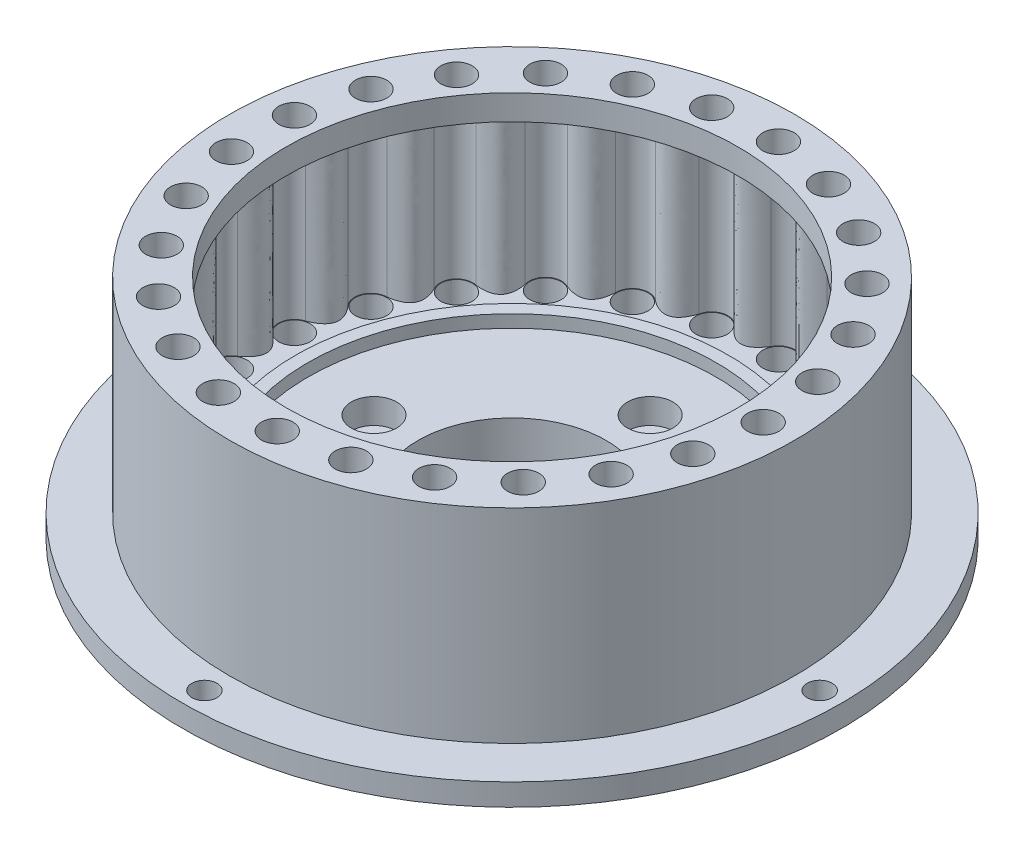
SolidWorks part; units mm, degrees
ref_plane "Front Plane" through (0, 0, 0) normal (0, 0, 1) x (1, 0, 0)
ref_plane "Top Plane" through (0, 0, 0) normal (0, 1, 0) x (1, 0, 0)
ref_plane "Right Plane" through (0, 0, 0) normal (1, 0, 0) x (0, 0, -1)
sketch "Sketch1" plane through (0, 0, 0) normal (0, 1, 0) x (1, 0, 0)
  circle A1 centre (0, 0) radius 45
  circle A2 centre (0, 0) radius 22 construction
  circle A3 centre (0, -22) radius 2
  circle A5 centre (-22, 0) radius 2
  circle A6 centre (0, 22) radius 2
  circle A7 centre (22, 0) radius 2
  point P15 (0, 0)
  dimension "D1" = 90
  dimension "D2" = 44
  dimension "D3" = 4
  dimension "D4" = 4
  dimension "D5" = 90
  dimension "D6" = 22
extrude "Boss-Extrude1" add sketch "Sketch1" along normal blind 6
sketch "Sketch2" plane through (0, 6, 0) normal (0, 1, 0) x (1, 0, 0)
  circle A0 centre (0, 0) radius 22 construction
  circle A1 centre (0, 22) radius 3.61
  circle A2 centre (22, 0) radius 3.61
  circle A3 centre (0, -22) radius 3.61
  circle A4 centre (-22, 0) radius 3.61
  point P14 (0, 0)
  dimension "D1" = 44
  dimension "D2" = 7.22
  dimension "D4" = 22
  dimension "D5" = 90
  dimension "D3" = 4
extrude "Cut-Extrude1" cut sketch "Sketch2" against normal blind 4
sketch "Sketch4" plane through (0, 6, 0) normal (0, 1, 0) x (1, 0, 0)
  circle A0 centre (0, 0) radius 15
  dimension "D1" = 30
extrude "Cut-Extrude2" cut sketch "Sketch4" against normal through all
sketch "Sketch5" plane through (0, 6, 0) normal (0, 1, 0) x (1, 0, 0)
  circle A0 centre (40, 0) radius 2.5
  circle A1 centre (38.7433, -9.9476) radius 2.5
  circle A2 centre (35.0523, -19.2701) radius 2.5
  circle A3 centre (29.1587, -27.3819) radius 2.5
  circle A4 centre (21.4331, -33.7731) radius 2.5
  circle A5 centre (12.3607, -38.0423) radius 2.5
  circle A6 centre (2.5116, -39.9211) radius 2.5
  circle A7 centre (-7.4953, -39.2915) radius 2.5
  circle A8 centre (-17.0312, -36.1931) radius 2.5
  circle A9 centre (-25.497, -30.8205) radius 2.5
  circle A10 centre (-32.3607, -23.5114) radius 2.5
  circle A11 centre (-37.1911, -14.725) radius 2.5
  circle A12 centre (-39.6846, -5.0133) radius 2.5
  circle A13 centre (-39.6846, 5.0133) radius 2.5
  circle A14 centre (-37.1911, 14.725) radius 2.5
  circle A15 centre (-32.3607, 23.5114) radius 2.5
  circle A16 centre (-25.497, 30.8205) radius 2.5
  circle A17 centre (-17.0312, 36.1931) radius 2.5
  circle A18 centre (-7.4953, 39.2915) radius 2.5
  circle A19 centre (2.5116, 39.9211) radius 2.5
  circle A20 centre (12.3607, 38.0423) radius 2.5
  circle A21 centre (21.4331, 33.7731) radius 2.5
  circle A22 centre (29.1587, 27.3819) radius 2.5
  circle A23 centre (35.0523, 19.2701) radius 2.5
  circle A24 centre (38.7433, 9.9476) radius 2.5
  point P53 (0, 0)
  dimension "D2" = 5
  dimension "D1" = 40
  dimension "D3" = 25
extrude "Cut-Extrude3" cut sketch "Sketch5" against normal blind 4
sketch "Sketch6" plane through (0, 6, 0) normal (0, 1, 0) x (1, 0, 0)
  circle A0 centre (0, 0) radius 32.5
  circle A1 centre (0, 0) radius 34.5
  dimension "D1" = 65
  dimension "D2" = 69
extrude "Boss-Extrude2" add sketch "Sketch6" along normal blind 2
sketch "Sketch7" plane through (0, 6, 0) normal (0, 1, 0) x (1, 0, 0)
  line L0 (0, 0) -> (35.0523, -19.2701) construction
  line L1 (0, 0) -> (27.3363, -25.6705) construction
  line L2 (35.0523, -19.2701) -> (34.7909, -21.7565) construction
  line L3 (29.1587, -27.3819) -> (31.4426, -26.365) construction
  line L4 (0, 0) -> (31.5517, -22.9236) construction
  circle A0 centre (35.0523, -19.2701) radius 2.5 construction
  circle A1 centre (38.7433, -9.9476) radius 2.5 construction
  circle A2 centre (40, 0) radius 2.5 construction
  circle A3 centre (38.7433, 9.9476) radius 2.5 construction
  circle A4 centre (35.0523, 19.2701) radius 2.5 construction
  circle A5 centre (29.1587, 27.3819) radius 2.5 construction
  circle A6 centre (21.4331, 33.7731) radius 2.5 construction
  circle A7 centre (12.3607, 38.0423) radius 2.5 construction
  circle A8 centre (2.5116, 39.9211) radius 2.5 construction
  circle A9 centre (-7.4953, 39.2915) radius 2.5 construction
  circle A10 centre (-17.0312, 36.1931) radius 2.5 construction
  circle A11 centre (-25.497, 30.8205) radius 2.5 construction
  circle A12 centre (-32.3607, 23.5114) radius 2.5 construction
  circle A13 centre (-37.1911, 14.725) radius 2.5 construction
  circle A14 centre (-39.6846, 5.0133) radius 2.5 construction
  circle A15 centre (-39.6846, -5.0133) radius 2.5 construction
  circle A16 centre (-37.1911, -14.725) radius 2.5 construction
  circle A17 centre (-32.3607, -23.5114) radius 2.5 construction
  circle A18 centre (-25.497, -30.8205) radius 2.5 construction
  circle A19 centre (-17.0312, -36.1931) radius 2.5 construction
  circle A20 centre (-7.4953, -39.2915) radius 2.5 construction
  circle A21 centre (2.5116, -39.9211) radius 2.5 construction
  circle A22 centre (12.3607, -38.0423) radius 2.5 construction
  circle A23 centre (21.4331, -33.7731) radius 2.5 construction
  circle A24 centre (29.1587, -27.3819) radius 2.5 construction
  arc A25 (34.7909, -21.7565) -> (37.0115, -17.7173) centre (35.0523, -19.2701) ccw construction
  arc A26 (39.1085, -12.4208) -> (40.2548, -7.9563) centre (38.7433, -9.9476) ccw construction
  arc A27 (40.9688, -2.3047) -> (40.9688, 2.3047) centre (40, 0) ccw construction
  arc A28 (40.2548, 7.9563) -> (39.1085, 12.4208) centre (38.7433, 9.9476) ccw construction
  arc A29 (37.0115, 17.7173) -> (34.7909, 21.7565) centre (35.0523, 19.2701) ccw construction
  arc A30 (31.4426, 26.365) -> (28.2873, 29.7251) centre (29.1587, 27.3819) ccw construction
  arc A31 (23.8981, 33.3562) -> (20.0063, 35.826) centre (21.4331, 33.7731) ccw construction
  arc A32 (14.8519, 38.2515) -> (10.4682, 39.6758) centre (12.3607, 38.0423) ccw construction
  arc A33 (4.8726, 40.7432) -> (0.2723, 41.0327) centre (2.5116, 39.9211) ccw construction
  arc A34 (-5.4129, 40.675) -> (-9.9406, 39.8113) centre (-7.4953, 39.2915) ccw construction
  arc A35 (-15.3583, 38.0509) -> (-19.529, 36.0884) centre (-17.0312, 36.1931) ccw construction
  arc A36 (-24.3387, 33.036) -> (-27.8903, 30.098) centre (-25.497, 30.8205) ccw construction
  arc A37 (-31.7898, 25.9454) -> (-34.4991, 22.2163) centre (-32.3607, 23.5114) ccw construction
  arc A38 (-37.2434, 17.2244) -> (-38.9402, 12.9388) centre (-37.1911, 14.725) ccw construction
  arc A39 (-40.3569, 7.4212) -> (-40.9346, 2.8483) centre (-39.6846, 5.0133) ccw construction
  arc A40 (-40.9346, -2.8483) -> (-40.3569, -7.4212) centre (-39.6846, -5.0133) ccw construction
  arc A41 (-38.9402, -12.9388) -> (-37.2434, -17.2244) centre (-37.1911, -14.725) ccw construction
  arc A42 (-34.4991, -22.2163) -> (-31.7898, -25.9454) centre (-32.3607, -23.5114) ccw construction
  arc A43 (-27.8903, -30.098) -> (-24.3387, -33.036) centre (-25.497, -30.8205) ccw construction
  arc A44 (-19.529, -36.0884) -> (-15.3583, -38.0509) centre (-17.0312, -36.1931) ccw construction
  arc A45 (-9.9406, -39.8113) -> (-5.4129, -40.675) centre (-7.4953, -39.2915) ccw construction
  arc A46 (0.2723, -41.0327) -> (4.8726, -40.7432) centre (2.5116, -39.9211) ccw construction
  arc A47 (10.4682, -39.6758) -> (14.8519, -38.2515) centre (12.3607, -38.0423) ccw construction
  arc A48 (20.0063, -35.826) -> (23.8981, -33.3562) centre (21.4331, -33.7731) ccw construction
  arc A49 (28.2873, -29.7251) -> (31.4426, -26.365) centre (29.1587, -27.3819) ccw construction
  arc A51 (33.4936, -21.8672) -> (35.0523, -19.2701) centre (0, 0) ccw construction
  arc A53 (23.9272, -32.0545) -> (27.0032, -29.5098) centre (0, 0) ccw construction
  arc A54 (15.2038, -36.9979) -> (18.8161, -35.2981) centre (0, 0) ccw construction
  arc A55 (9.9601, -38.7401) -> (14.713, -37.1958) centre (0, 0) ccw construction
  arc A56 (5.5252, -39.6166) -> (9.4467, -38.8685) centre (0, 0) ccw construction
  arc A57 (-5.0261, -39.683) -> (5.0006, -39.6862) centre (0, 0) ccw construction
  arc A58 (-14.7369, -37.1863) -> (-10.4469, -38.6117) centre (0, 0) ccw construction
  arc A59 (-23.0917, -32.6615) -> (-22.9047, -32.7929) centre (0, 0) ccw construction
  arc A60 (-30.4888, -25.8927) -> (-27.756, -28.8029) centre (0, 0) ccw construction
  arc A61 (-35.9702, -17.4969) -> (-34.047, -20.9953) centre (0, 0) ccw construction
  arc A62 (-39.1915, -8.0018) -> (-38.1986, -11.8686) centre (0, 0) ccw construction
  arc A63 (-39.9502, 1.9961) -> (-39.9502, -1.9961) centre (0, 0) ccw construction
  arc A64 (-38.1986, 11.8686) -> (-39.1915, 8.0018) centre (0, 0) ccw construction
  arc A65 (-36.1986, 17.0195) -> (-38.0383, 12.3729) centre (0, 0) ccw construction
  arc A66 (-34.047, 20.9953) -> (-35.9702, 17.4969) centre (0, 0) ccw construction
  arc A67 (-27.756, 28.8029) -> (-30.4888, 25.8927) centre (0, 0) ccw construction
  arc A68 (-19.2589, 35.0585) -> (-23.0917, 32.6615) centre (0, 0) ccw construction
  arc A69 (-9.9351, 38.7465) -> (-14.7369, 37.1863) centre (0, 0) ccw construction
  arc A70 (-0.5163, 39.9967) -> (-5.0261, 39.683) centre (0, 0) ccw construction
  arc A71 (9.4467, 38.8685) -> (0.0129, 40) centre (0, 0) ccw construction
  arc A72 (18.8161, 35.2981) -> (15.2038, 36.9979) centre (0, 0) ccw construction
  arc A73 (27.0032, 29.5098) -> (23.9272, 32.0545) centre (0, 0) ccw construction
  arc A74 (33.4936, 21.8672) -> (30.8123, 25.5069) centre (0, 0) ccw construction
  arc A75 (37.8795, 12.8507) -> (36.4099, 16.5626) centre (0, 0) ccw construction
  arc A76 (39.8853, 3.0267) -> (39.2891, 7.5079) centre (0, 0) ccw construction
  arc A77 (39.385, -6.9875) -> (39.9219, -2.4988) centre (0, 0) ccw construction
  arc A78 (36.1876, -17.0428) -> (37.8795, -12.8507) centre (0, 0) ccw construction
  circle A79 centre (0, 0) radius 45
  arc A80 (34.7861, -21.8565) -> (37.0934, -17.6596) centre (35.0523, -19.2701) ccw
  arc A81 (39.1287, -12.5189) -> (40.3198, -7.88) centre (38.7433, -9.9476) ccw
  arc A82 (41.0127, -2.3947) -> (41.0127, 2.3947) centre (40, 0) ccw
  arc A83 (40.3198, 7.88) -> (39.1287, 12.5189) centre (38.7433, 9.9476) ccw
  arc A84 (37.0934, 17.6596) -> (34.7861, 21.8565) centre (35.0523, 19.2701) ccw
  arc A85 (31.5362, 26.3295) -> (28.2577, 29.8208) centre (29.1587, 27.3819) ccw
  arc A86 (23.9976, 33.3451) -> (19.9538, 35.9113) centre (21.4331, 33.7731) ccw
  arc A87 (14.9511, 38.2654) -> (10.3962, 39.7454) centre (12.3607, 38.0423) ccw
  arc A88 (4.9651, 40.7814) -> (0.1853, 41.0822) centre (2.5116, 39.9211) ccw
  arc A89 (-5.3328, 40.735) -> (-10.0373, 39.8376) centre (-7.4953, 39.2915) ccw
  arc A90 (-15.2956, 38.129) -> (-19.6291, 36.0898) centre (-17.0312, 36.1931) ccw
  arc A91 (-24.2974, 33.1273) -> (-27.9876, 30.0744) centre (-25.497, 30.8205) ccw
  arc A92 (-31.7724, 26.044) -> (-34.5875, 22.1694) centre (-32.3607, 23.5114) ccw
  arc A93 (-37.2511, 17.3243) -> (-39.0142, 12.8713) centre (-37.1911, 14.725) ccw
  arc A94 (-40.3892, 7.516) -> (-40.9895, 2.7645) centre (-39.6846, 5.0133) ccw
  arc A95 (-40.9895, -2.7645) -> (-40.3892, -7.516) centre (-39.6846, -5.0133) ccw
  arc A96 (-39.0142, -12.8713) -> (-37.2511, -17.3243) centre (-37.1911, -14.725) ccw
  arc A97 (-34.5875, -22.1694) -> (-31.7724, -26.044) centre (-32.3607, -23.5114) ccw
  arc A98 (-27.9876, -30.0744) -> (-24.2974, -33.1273) centre (-25.497, -30.8205) ccw
  arc A99 (-19.6291, -36.0898) -> (-15.2956, -38.129) centre (-17.0312, -36.1931) ccw
  arc A100 (-10.0373, -39.8376) -> (-5.3328, -40.735) centre (-7.4953, -39.2915) ccw
  arc A101 (0.1853, -41.0822) -> (4.9651, -40.7814) centre (2.5116, -39.9211) ccw
  arc A102 (10.3962, -39.7454) -> (14.9511, -38.2654) centre (12.3607, -38.0423) ccw
  arc A103 (19.9538, -35.9113) -> (23.9976, -33.3451) centre (21.4331, -33.7731) ccw
  arc A104 (28.2577, -29.8208) -> (31.5362, -26.3295) centre (29.1587, -27.3819) ccw
  spline S0 degree 2 poles (34.7909, -21.7565) (29.9865, -21.7865) (31.4426, -26.365) knots 0 0 0 1 1 1 construction
  spline S1 degree 2 poles (28.2873, -29.7251) (23.6264, -28.5594) (23.8981, -33.3562) knots 0 0 0 1 1 1 construction
  spline S2 degree 2 poles (20.0063, -35.826) (15.7817, -33.5378) (14.8519, -38.2515) knots 0 0 0 1 1 1 construction
  spline S3 degree 2 poles (10.4682, -39.6758) (6.9454, -36.4089) (4.8726, -40.7432) knots 0 0 0 1 1 1 construction
  spline S4 degree 2 poles (0.2723, -41.0327) (-2.3274, -36.9923) (-5.4129, -40.675) knots 0 0 0 1 1 1 construction
  spline S5 degree 2 poles (-9.9406, -39.8113) (-11.4538, -35.2513) (-15.3583, -38.0509) knots 0 0 0 1 1 1 construction
  spline S6 degree 2 poles (-19.529, -36.0884) (-19.8606, -31.2954) (-24.3387, -33.036) knots 0 0 0 1 1 1 construction
  spline S7 degree 2 poles (-27.8903, -30.098) (-27.0195, -25.373) (-31.7898, -25.9454) knots 0 0 0 1 1 1 construction
  spline S8 degree 2 poles (-34.4991, -22.2163) (-32.4807, -17.8564) (-37.2434, -17.2244) knots 0 0 0 1 1 1 construction
  spline S9 degree 2 poles (-38.9402, -12.9388) (-35.9009, -9.2178) (-40.3569, -7.4212) knots 0 0 0 1 1 1 construction
  spline S10 degree 2 poles (-40.9346, -2.8483) (-37.0654, 0) (-40.9346, 2.8483) knots 0 0 0 1 1 1 construction
  spline S11 degree 2 poles (-40.3569, 7.4212) (-35.9009, 9.2178) (-38.9402, 12.9388) knots 0 0 0 1 1 1 construction
  spline S12 degree 2 poles (-37.2434, 17.2244) (-32.4807, 17.8564) (-34.4991, 22.2163) knots 0 0 0 1 1 1 construction
  spline S13 degree 2 poles (-31.7898, 25.9454) (-27.0195, 25.373) (-27.8903, 30.098) knots 0 0 0 1 1 1 construction
  spline S14 degree 2 poles (-24.3387, 33.036) (-19.8606, 31.2954) (-19.529, 36.0884) knots 0 0 0 1 1 1 construction
  spline S15 degree 2 poles (-15.3583, 38.0509) (-11.4538, 35.2513) (-9.9406, 39.8113) knots 0 0 0 1 1 1 construction
  spline S16 degree 2 poles (-5.4129, 40.675) (-2.3274, 36.9923) (0.2723, 41.0327) knots 0 0 0 1 1 1 construction
  spline S17 degree 2 poles (4.8726, 40.7432) (6.9454, 36.4089) (10.4682, 39.6758) knots 0 0 0 1 1 1 construction
  spline S18 degree 2 poles (14.8519, 38.2515) (15.7817, 33.5378) (20.0063, 35.826) knots 0 0 0 1 1 1 construction
  spline S19 degree 2 poles (23.8981, 33.3562) (23.6264, 28.5594) (28.2873, 29.7251) knots 0 0 0 1 1 1 construction
  spline S20 degree 2 poles (31.4426, 26.365) (29.9865, 21.7865) (34.7909, 21.7565) knots 0 0 0 1 1 1 construction
  spline S21 degree 2 poles (37.0115, 17.7173) (34.4625, 13.6447) (39.1085, 12.4208) knots 0 0 0 1 1 1 construction
  spline S22 degree 2 poles (40.2548, 7.9563) (36.7731, 4.6455) (40.9688, 2.3047) knots 0 0 0 1 1 1 construction
  spline S23 degree 2 poles (40.9688, -2.3047) (36.7731, -4.6455) (40.2548, -7.9563) knots 0 0 0 1 1 1 construction
  spline S24 degree 2 poles (39.1085, -12.4208) (34.4625, -13.6447) (37.0115, -17.7173) knots 0 0 0 1 1 1 construction
  spline S25 degree 1 poles (39.1287, -12.5189) (37.0934, -17.6596) knots 0 0 1 1 construction
  spline S26 degree 1 poles (41.0127, -2.3947) (40.3198, -7.88) knots 0 0 1 1 construction
  spline S27 degree 1 poles (40.3198, 7.88) (41.0127, 2.3947) knots 0 0 1 1 construction
  spline S28 degree 1 poles (37.0934, 17.6596) (39.1287, 12.5189) knots 0 0 1 1 construction
  spline S29 degree 1 poles (31.5362, 26.3295) (34.7861, 21.8565) knots 0 0 1 1 construction
  spline S30 degree 1 poles (23.9976, 33.3451) (28.2577, 29.8208) knots 0 0 1 1 construction
  spline S31 degree 1 poles (14.9511, 38.2654) (19.9538, 35.9113) knots 0 0 1 1 construction
  spline S32 degree 1 poles (4.9651, 40.7814) (10.3962, 39.7454) knots 0 0 1 1 construction
  spline S33 degree 1 poles (-5.3328, 40.735) (0.1853, 41.0822) knots 0 0 1 1 construction
  spline S34 degree 1 poles (-15.2956, 38.129) (-10.0373, 39.8376) knots 0 0 1 1 construction
  spline S35 degree 1 poles (-24.2974, 33.1273) (-19.6291, 36.0898) knots 0 0 1 1 construction
  spline S36 degree 1 poles (-31.7724, 26.044) (-27.9876, 30.0744) knots 0 0 1 1 construction
  spline S37 degree 1 poles (-37.2511, 17.3243) (-34.5875, 22.1694) knots 0 0 1 1 construction
  spline S38 degree 1 poles (-40.3892, 7.516) (-39.0142, 12.8713) knots 0 0 1 1 construction
  spline S39 degree 1 poles (-40.9895, -2.7645) (-40.9895, 2.7645) knots 0 0 1 1 construction
  spline S40 degree 1 poles (-39.0142, -12.8713) (-40.3892, -7.516) knots 0 0 1 1 construction
  spline S41 degree 1 poles (-34.5875, -22.1694) (-37.2511, -17.3243) knots 0 0 1 1 construction
  spline S42 degree 1 poles (-27.9876, -30.0744) (-31.7724, -26.044) knots 0 0 1 1 construction
  spline S43 degree 1 poles (-19.6291, -36.0898) (-24.2974, -33.1273) knots 0 0 1 1 construction
  spline S44 degree 1 poles (-10.0373, -39.8376) (-15.2956, -38.129) knots 0 0 1 1 construction
  spline S45 degree 1 poles (0.1853, -41.0822) (-5.3328, -40.735) knots 0 0 1 1 construction
  spline S46 degree 1 poles (10.3962, -39.7454) (4.9651, -40.7814) knots 0 0 1 1 construction
  spline S47 degree 1 poles (19.9538, -35.9113) (14.9511, -38.2654) knots 0 0 1 1 construction
  spline S48 degree 1 poles (28.2577, -29.8208) (23.9976, -33.3451) knots 0 0 1 1 construction
  spline S49 degree 1 poles (34.7861, -21.8565) (31.5362, -26.3295) knots 0 0 1 1 construction
  spline S50 degree 3 poles (37.0934, -17.6596) (36.9928, -17.4988) (36.7956, -17.161) (36.4917, -16.5417) (36.2467, -15.8185) (36.1759, -15.0518) (36.3187, -14.3796) (36.6748, -13.7918) (37.2512, -13.2814) (37.9249, -12.9219) (38.5703, -12.6785) (38.9453, -12.5673) (39.1287, -12.5189) knots 0.000577 0.000577 0.000577 0.000577 0.063005 0.125433 0.250288 0.375144 0.5 0.624856 0.749712 0.874567 0.936995 0.999423 0.999423 0.999423 0.999423
  spline S51 degree 3 poles (40.3198, -7.88) (40.1824, -7.7493) (39.9074, -7.4711) (39.459, -6.9469) (39.0418, -6.3073) (38.7826, -5.5824) (38.7538, -4.8957) (38.9524, -4.2379) (39.3838, -3.6001) (39.947, -3.0844) (40.5116, -2.6882) (40.8472, -2.4872) (41.0127, -2.3947) knots 0.000577 0.000577 0.000577 0.000577 0.063005 0.125433 0.250288 0.375144 0.5 0.624856 0.749712 0.874567 0.936995 0.999423 0.999423 0.999423 0.999423
  spline S52 degree 3 poles (41.0127, 2.3947) (40.8472, 2.4872) (40.5116, 2.6882) (39.947, 3.0844) (39.3838, 3.6001) (38.9524, 4.2379) (38.7538, 4.8957) (38.7826, 5.5824) (39.0418, 6.3073) (39.459, 6.9469) (39.9074, 7.4711) (40.1824, 7.7493) (40.3198, 7.88) knots 0.000577 0.000577 0.000577 0.000577 0.063005 0.125433 0.250288 0.375144 0.5 0.624856 0.749712 0.874567 0.936995 0.999423 0.999423 0.999423 0.999423
  spline S53 degree 3 poles (39.1287, 12.5189) (38.9453, 12.5673) (38.5703, 12.6785) (37.9249, 12.9219) (37.2512, 13.2814) (36.6748, 13.7918) (36.3187, 14.3796) (36.1759, 15.0518) (36.2467, 15.8185) (36.4917, 16.5417) (36.7956, 17.161) (36.9928, 17.4988) (37.0934, 17.6596) knots 0.000577 0.000577 0.000577 0.000577 0.063005 0.125433 0.250288 0.375144 0.5 0.624856 0.749712 0.874567 0.936995 0.999423 0.999423 0.999423 0.999423
  spline S54 degree 3 poles (34.7861, 21.8565) (34.5964, 21.8578) (34.2055, 21.8722) (33.5199, 21.9475) (32.7779, 22.1281) (32.0927, 22.4791) (31.6016, 22.9599) (31.2961, 23.5755) (31.174, 24.3357) (31.2315, 25.0971) (31.3718, 25.7725) (31.4789, 26.1488) (31.5362, 26.3295) knots 0.000577 0.000577 0.000577 0.000577 0.063005 0.125433 0.250288 0.375144 0.5 0.624856 0.749712 0.874567 0.936995 0.999423 0.999423 0.999423 0.999423
  spline S55 degree 3 poles (28.2577, 29.8208) (28.0737, 29.7749) (27.6915, 29.6917) (27.0087, 29.594) (26.2451, 29.5845) (25.4941, 29.754) (24.8989, 30.0976) (24.4499, 30.6179) (24.1426, 31.3238) (24.0089, 32.0756) (23.9769, 32.7647) (23.987, 33.1557) (23.9976, 33.3451) knots 0.000577 0.000577 0.000577 0.000577 0.063005 0.125433 0.250288 0.375144 0.5 0.624856 0.749712 0.874567 0.936995 0.999423 0.999423 0.999423 0.999423
  spline S56 degree 3 poles (19.9538, 35.9113) (19.787, 35.8211) (19.4375, 35.6454) (18.8004, 35.3811) (18.0632, 35.1819) (17.2936, 35.1594) (16.6317, 35.3442) (16.0674, 35.7364) (15.5942, 36.3437) (15.2777, 37.0387) (15.0754, 37.6981) (14.9879, 38.0794) (14.9511, 38.2654) knots 0.000577 0.000577 0.000577 0.000577 0.063005 0.125433 0.250288 0.375144 0.5 0.624856 0.749712 0.874567 0.936995 0.999423 0.999423 0.999423 0.999423
  spline S57 degree 3 poles (10.3962, 39.7454) (10.257, 39.6165) (9.9622, 39.3595) (9.4108, 38.945) (8.7463, 38.5687) (8.0065, 38.3555) (7.3194, 38.3699) (6.6753, 38.6095) (6.0659, 39.08) (5.5866, 39.6745) (5.2266, 40.2629) (5.0471, 40.6104) (4.9651, 40.7814) knots 0.000577 0.000577 0.000577 0.000577 0.063005 0.125433 0.250288 0.375144 0.5 0.624856 0.749712 0.874567 0.936995 0.999423 0.999423 0.999423 0.999423
  spline S58 degree 3 poles (0.1853, 41.0822) (0.0826, 40.9227) (-0.1391, 40.6004) (-0.57, 40.0618) (-1.1201, 39.5321) (-1.7837, 39.1417) (-2.4527, 38.9847) (-3.1362, 39.0566) (-3.8434, 39.3608) (-4.4555, 39.8174) (-4.9506, 40.2977) (-5.2109, 40.5897) (-5.3328, 40.735) knots 0.000577 0.000577 0.000577 0.000577 0.063005 0.125433 0.250288 0.375144 0.5 0.624856 0.749712 0.874567 0.936995 0.999423 0.999423 0.999423 0.999423
  spline S59 degree 3 poles (-10.0373, 39.8376) (-10.0971, 39.6576) (-10.2317, 39.2903) (-10.5151, 38.6614) (-10.9161, 38.0116) (-11.4618, 37.4684) (-12.0708, 37.15) (-12.7506, 37.0496) (-13.5113, 37.1684) (-14.2177, 37.4584) (-14.8167, 37.8005) (-15.1414, 38.0186) (-15.2956, 38.129) knots 0.000577 0.000577 0.000577 0.000577 0.063005 0.125433 0.250288 0.375144 0.5 0.624856 0.749712 0.874567 0.936995 0.999423 0.999423 0.999423 0.999423
  spline S60 degree 3 poles (-19.6291, 36.0898) (-19.6423, 35.9006) (-19.6813, 35.5114) (-19.7995, 34.8318) (-20.0263, 34.1027) (-20.4197, 33.4408) (-20.9303, 32.981) (-21.5639, 32.7147) (-22.3302, 32.6406) (-23.0866, 32.7458) (-23.7518, 32.9282) (-24.1206, 33.0586) (-24.2974, 33.1273) knots 0.000577 0.000577 0.000577 0.000577 0.063005 0.125433 0.250288 0.375144 0.5 0.624856 0.749712 0.874567 0.936995 0.999423 0.999423 0.999423 0.999423
  spline S61 degree 3 poles (-27.9876, 30.0744) (-27.9533, 29.8879) (-27.8943, 29.5012) (-27.8397, 28.8136) (-27.8781, 28.0509) (-28.0945, 27.3121) (-28.4748, 26.7396) (-29.0222, 26.3242) (-29.7461, 26.0618) (-30.5048, 25.9756) (-31.1945, 25.9869) (-31.5841, 26.0215) (-31.7724, 26.044) knots 0.000577 0.000577 0.000577 0.000577 0.063005 0.125433 0.250288 0.375144 0.5 0.624856 0.749712 0.874567 0.936995 0.999423 0.999423 0.999423 0.999423
  spline S62 degree 3 poles (-34.5875, 22.1694) (-34.508, 21.9972) (-34.3546, 21.6373) (-34.1308, 20.9849) (-33.9783, 20.2367) (-34.0041, 19.4672) (-34.2301, 18.8182) (-34.657, 18.2796) (-35.2928, 17.8455) (-36.0063, 17.5733) (-36.6771, 17.4127) (-37.0631, 17.3493) (-37.2511, 17.3243) knots 0.000577 0.000577 0.000577 0.000577 0.063005 0.125433 0.250288 0.375144 0.5 0.624856 0.749712 0.874567 0.936995 0.999423 0.999423 0.999423 0.999423
  spline S63 degree 3 poles (-39.0142, 12.8713) (-38.8943, 12.7243) (-38.6563, 12.4139) (-38.2772, 11.8376) (-37.9434, 11.1508) (-37.7771, 10.3991) (-37.8346, 9.7143) (-38.1141, 9.0865) (-38.622, 8.5078) (-39.2454, 8.0668) (-39.8552, 7.7444) (-40.2133, 7.587) (-40.3892, 7.516) knots 0.000577 0.000577 0.000577 0.000577 0.063005 0.125433 0.250288 0.375144 0.5 0.624856 0.749712 0.874567 0.936995 0.999423 0.999423 0.999423 0.999423
  spline S64 degree 3 poles (-40.9895, 2.7645) (-40.8368, 2.652) (-40.5291, 2.4105) (-40.0186, 1.9466) (-39.5245, 1.3644) (-39.1764, 0.6776) (-39.0618, 0) (-39.1764, -0.6776) (-39.5245, -1.3644) (-40.0186, -1.9466) (-40.5291, -2.4105) (-40.8368, -2.652) (-40.9895, -2.7645) knots 0.000577 0.000577 0.000577 0.000577 0.063005 0.125433 0.250288 0.375144 0.5 0.624856 0.749712 0.874567 0.936995 0.999423 0.999423 0.999423 0.999423
  spline S65 degree 3 poles (-40.3892, -7.516) (-40.2133, -7.587) (-39.8552, -7.7444) (-39.2454, -8.0668) (-38.622, -8.5078) (-38.1141, -9.0865) (-37.8346, -9.7143) (-37.7771, -10.3991) (-37.9434, -11.1508) (-38.2772, -11.8376) (-38.6563, -12.4139) (-38.8943, -12.7243) (-39.0142, -12.8713) knots 0.000577 0.000577 0.000577 0.000577 0.063005 0.125433 0.250288 0.375144 0.5 0.624856 0.749712 0.874567 0.936995 0.999423 0.999423 0.999423 0.999423
  spline S66 degree 3 poles (-37.2511, -17.3243) (-37.0631, -17.3493) (-36.6771, -17.4127) (-36.0063, -17.5733) (-35.2928, -17.8455) (-34.657, -18.2796) (-34.2301, -18.8182) (-34.0041, -19.4672) (-33.9783, -20.2367) (-34.1308, -20.9849) (-34.3546, -21.6373) (-34.508, -21.9972) (-34.5875, -22.1694) knots 0.000577 0.000577 0.000577 0.000577 0.063005 0.125433 0.250288 0.375144 0.5 0.624856 0.749712 0.874567 0.936995 0.999423 0.999423 0.999423 0.999423
  spline S67 degree 3 poles (-31.7724, -26.044) (-31.5841, -26.0215) (-31.1945, -25.9869) (-30.5048, -25.9756) (-29.7461, -26.0618) (-29.0222, -26.3242) (-28.4748, -26.7396) (-28.0945, -27.3121) (-27.8781, -28.0509) (-27.8397, -28.8136) (-27.8943, -29.5012) (-27.9533, -29.8879) (-27.9876, -30.0744) knots 0.000577 0.000577 0.000577 0.000577 0.063005 0.125433 0.250288 0.375144 0.5 0.624856 0.749712 0.874567 0.936995 0.999423 0.999423 0.999423 0.999423
  spline S68 degree 3 poles (-24.2974, -33.1273) (-24.1206, -33.0586) (-23.7518, -32.9282) (-23.0866, -32.7458) (-22.3302, -32.6406) (-21.5639, -32.7147) (-20.9303, -32.981) (-20.4197, -33.4408) (-20.0263, -34.1027) (-19.7995, -34.8318) (-19.6813, -35.5114) (-19.6423, -35.9006) (-19.6291, -36.0898) knots 0.000577 0.000577 0.000577 0.000577 0.063005 0.125433 0.250288 0.375144 0.5 0.624856 0.749712 0.874567 0.936995 0.999423 0.999423 0.999423 0.999423
  spline S69 degree 3 poles (-15.2956, -38.129) (-15.1414, -38.0186) (-14.8167, -37.8005) (-14.2177, -37.4584) (-13.5113, -37.1684) (-12.7506, -37.0496) (-12.0708, -37.15) (-11.4618, -37.4684) (-10.9161, -38.0116) (-10.5151, -38.6614) (-10.2317, -39.2903) (-10.0971, -39.6576) (-10.0373, -39.8376) knots 0.000577 0.000577 0.000577 0.000577 0.063005 0.125433 0.250288 0.375144 0.5 0.624856 0.749712 0.874567 0.936995 0.999423 0.999423 0.999423 0.999423
  spline S70 degree 3 poles (-5.3328, -40.735) (-5.2109, -40.5897) (-4.9506, -40.2977) (-4.4555, -39.8174) (-3.8434, -39.3608) (-3.1362, -39.0566) (-2.4527, -38.9847) (-1.7837, -39.1417) (-1.1201, -39.5321) (-0.57, -40.0618) (-0.1391, -40.6004) (0.0826, -40.9227) (0.1853, -41.0822) knots 0.000577 0.000577 0.000577 0.000577 0.063005 0.125433 0.250288 0.375144 0.5 0.624856 0.749712 0.874567 0.936995 0.999423 0.999423 0.999423 0.999423
  spline S71 degree 3 poles (4.9651, -40.7814) (5.0471, -40.6104) (5.2266, -40.2629) (5.5866, -39.6745) (6.0659, -39.08) (6.6753, -38.6095) (7.3194, -38.3699) (8.0065, -38.3555) (8.7463, -38.5687) (9.4108, -38.945) (9.9622, -39.3595) (10.257, -39.6165) (10.3962, -39.7454) knots 0.000577 0.000577 0.000577 0.000577 0.063005 0.125433 0.250288 0.375144 0.5 0.624856 0.749712 0.874567 0.936995 0.999423 0.999423 0.999423 0.999423
  spline S72 degree 3 poles (14.9511, -38.2654) (14.9879, -38.0794) (15.0754, -37.6981) (15.2777, -37.0387) (15.5942, -36.3437) (16.0674, -35.7364) (16.6317, -35.3442) (17.2936, -35.1594) (18.0632, -35.1819) (18.8004, -35.3811) (19.4375, -35.6454) (19.787, -35.8211) (19.9538, -35.9113) knots 0.000577 0.000577 0.000577 0.000577 0.063005 0.125433 0.250288 0.375144 0.5 0.624856 0.749712 0.874567 0.936995 0.999423 0.999423 0.999423 0.999423
  spline S73 degree 3 poles (23.9976, -33.3451) (23.987, -33.1557) (23.9769, -32.7647) (24.0089, -32.0756) (24.1426, -31.3238) (24.4499, -30.6179) (24.8989, -30.0976) (25.4941, -29.754) (26.2451, -29.5845) (27.0087, -29.594) (27.6915, -29.6917) (28.0737, -29.7749) (28.2577, -29.8208) knots 0.000577 0.000577 0.000577 0.000577 0.063005 0.125433 0.250288 0.375144 0.5 0.624856 0.749712 0.874567 0.936995 0.999423 0.999423 0.999423 0.999423
  spline S74 degree 3 poles (31.5362, -26.3295) (31.4789, -26.1488) (31.3718, -25.7725) (31.2315, -25.0971) (31.174, -24.3357) (31.2961, -23.5755) (31.6016, -22.9599) (32.0927, -22.4791) (32.7779, -22.1281) (33.5199, -21.9475) (34.2055, -21.8722) (34.5964, -21.8578) (34.7861, -21.8565) knots 0.000577 0.000577 0.000577 0.000577 0.063005 0.125433 0.250288 0.375144 0.5 0.624856 0.749712 0.874567 0.936995 0.999423 0.999423 0.999423 0.999423
  point P158 (0, 0)
  dimension "D1" = 7.2
  dimension "D2" = 0.1
extrude "Boss-Extrude4" add sketch "Sketch7" along normal blind 30
sketch "Sketch8" plane through (0, 36, 0) normal (0, 1, 0) x (1, 0, 0)
  circle A0 centre (0, 0) radius 36
  circle A1 centre (0, 0) radius 45
  dimension "D1" = 72
extrude "Boss-Extrude5" add sketch "Sketch8" against normal blind 4
sketch "Sketch9" plane through (0, 36, 0) normal (0, 1, 0) x (1, 0, 0)
  circle A0 centre (-17.0312, 36.1931) radius 2.5 construction
  circle A1 centre (-7.4953, 39.2915) radius 2.5 construction
  circle A2 centre (12.3607, 38.0423) radius 2.5 construction
  circle A3 centre (21.4331, 33.7731) radius 2.5 construction
  circle A4 centre (29.1587, 27.3819) radius 2.5 construction
  circle A5 centre (35.0523, 19.2701) radius 2.5 construction
  circle A6 centre (38.7433, 9.9476) radius 2.5 construction
  circle A7 centre (40, 0) radius 2.5 construction
  circle A8 centre (38.7433, -9.9476) radius 2.5 construction
  circle A9 centre (35.0523, -19.2701) radius 2.5 construction
  circle A10 centre (29.1587, -27.3819) radius 2.5 construction
  circle A11 centre (-7.4953, -39.2915) radius 2.5 construction
  circle A12 centre (12.3607, -38.0423) radius 2.5 construction
  circle A13 centre (2.5116, 39.9211) radius 2.5 construction
  circle A14 centre (-25.497, 30.8205) radius 2.5 construction
  circle A15 centre (-32.3607, 23.5114) radius 2.5 construction
  circle A16 centre (-37.1911, 14.725) radius 2.5 construction
  circle A17 centre (-39.6846, 5.0133) radius 2.5 construction
  circle A18 centre (-39.6846, -5.0133) radius 2.5 construction
  circle A19 centre (-37.1911, -14.725) radius 2.5 construction
  circle A20 centre (-32.3607, -23.5114) radius 2.5 construction
  circle A21 centre (-25.497, -30.8205) radius 2.5 construction
  circle A22 centre (-17.0312, -36.1931) radius 2.5 construction
  circle A23 centre (2.5116, -39.9211) radius 2.5 construction
  circle A24 centre (21.4331, -33.7731) radius 2.5 construction
  circle A25 centre (-17.0312, 36.1931) radius 2.5
  circle A26 centre (-7.4953, 39.2915) radius 2.5
  circle A27 centre (12.3607, 38.0423) radius 2.5
  circle A28 centre (21.4331, 33.7731) radius 2.5
  circle A29 centre (29.1587, 27.3819) radius 2.5
  circle A30 centre (35.0523, 19.2701) radius 2.5
  circle A31 centre (38.7433, 9.9476) radius 2.5
  circle A32 centre (40, 0) radius 2.5
  circle A33 centre (38.7433, -9.9476) radius 2.5
  circle A34 centre (35.0523, -19.2701) radius 2.5
  circle A35 centre (29.1587, -27.3819) radius 2.5
  circle A36 centre (-7.4953, -39.2915) radius 2.5
  circle A37 centre (12.3607, -38.0423) radius 2.5
  circle A38 centre (2.5116, 39.9211) radius 2.5
  circle A39 centre (-25.497, 30.8205) radius 2.5
  circle A40 centre (-32.3607, 23.5114) radius 2.5
  circle A41 centre (-37.1911, 14.725) radius 2.5
  circle A42 centre (-39.6846, 5.0133) radius 2.5
  circle A43 centre (-39.6846, -5.0133) radius 2.5
  circle A44 centre (-37.1911, -14.725) radius 2.5
  circle A45 centre (-32.3607, -23.5114) radius 2.5
  circle A46 centre (-25.497, -30.8205) radius 2.5
  circle A47 centre (-17.0312, -36.1931) radius 2.5
  circle A48 centre (2.5116, -39.9211) radius 2.5
  circle A49 centre (21.4331, -33.7731) radius 2.5
extrude "Cut-Extrude4" cut sketch "Sketch9" against normal blind 4
sketch "Sketch11" plane through (0, 0, 0) normal (0, -1, 0) x (1, 0, 0)
  circle A0 centre (0, 0) radius 52.5
  circle A1 centre (0, 0) radius 45
  circle A2 centre (0, 0) radius 45
  dimension "D2" = 105
  dimension "D1" = 0
extrude "Boss-Extrude7" add sketch "Sketch11" against normal blind 3.5
sketch "Sketch12" plane through (0, 3.5, 0) normal (0, 1, 0) x (1, 0, 0)
  circle A0 centre (0, 0) radius 49 construction
  circle A1 centre (0, -49) radius 2
  circle A2 centre (-49, 0) radius 2
  circle A3 centre (0, 49) radius 2
  circle A4 centre (49, 0) radius 2
  point P14 (0, 0)
  dimension "D1" = 98
  dimension "D2" = 4
extrude "Cut-Extrude5" cut sketch "Sketch12" against normal blind 5
